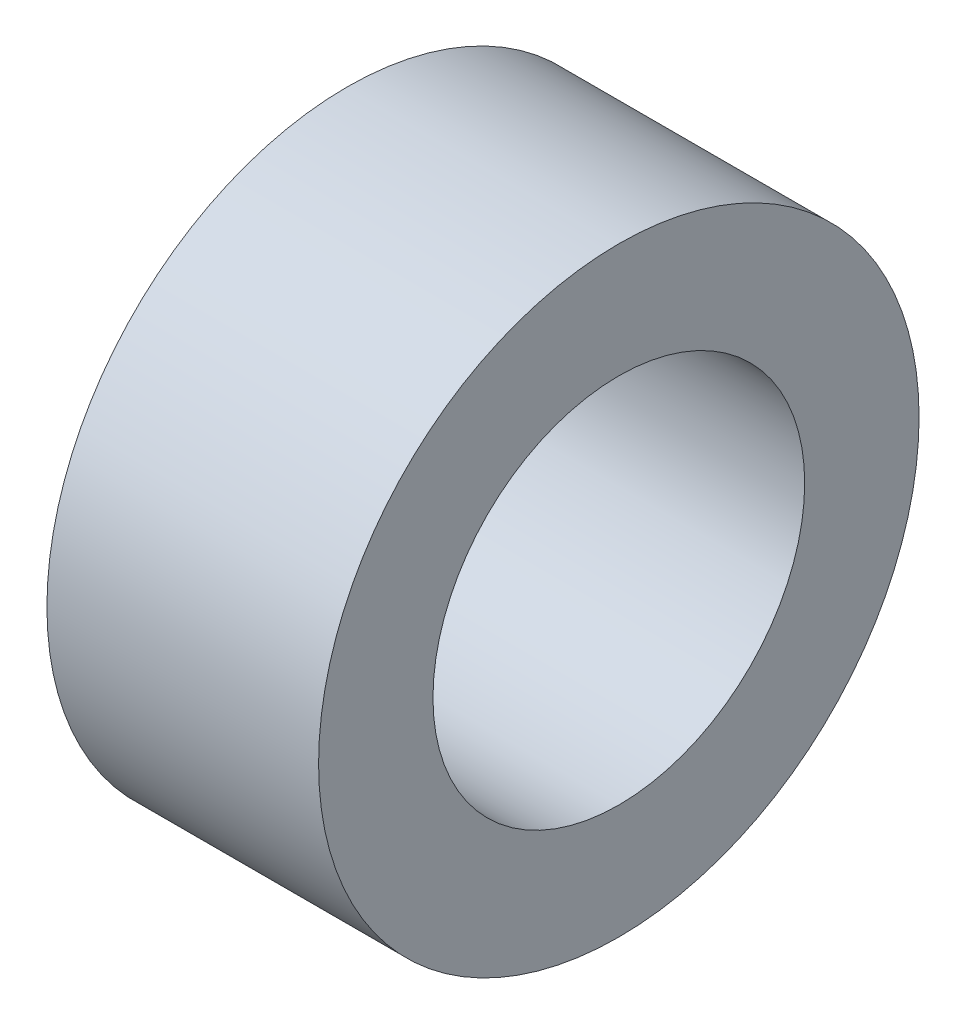
SolidWorks part; units mm, degrees
material "Rubber"
ref_plane "Front" through (0, 0, 0) normal (0, 0, 1) x (1, 0, 0)
ref_plane "Top" through (0, 0, 0) normal (0, 1, 0) x (1, 0, 0)
ref_plane "Right" through (0, 0, 0) normal (1, 0, 0) x (0, 0, -1)
sketch "Sketch1" plane through (0, 0, 0) normal (0, 1, 0) x (1, 0, 0)
  line L0 (0, 0) -> (19, 0)
  dimension "D1" = 19
revolve "Revolve-Thin1" add sketch "Sketch1" angle 360 about L0 wall 21
sketch "Sketch2" plane through (0, 0, 0) normal (-1, 0, 0) x (0, 0, 1)
  circle A0 centre (0, 0) radius 13
  dimension "D1" = 26
extrude "Cut-Extrude1" cut sketch "Sketch2" against normal through all
